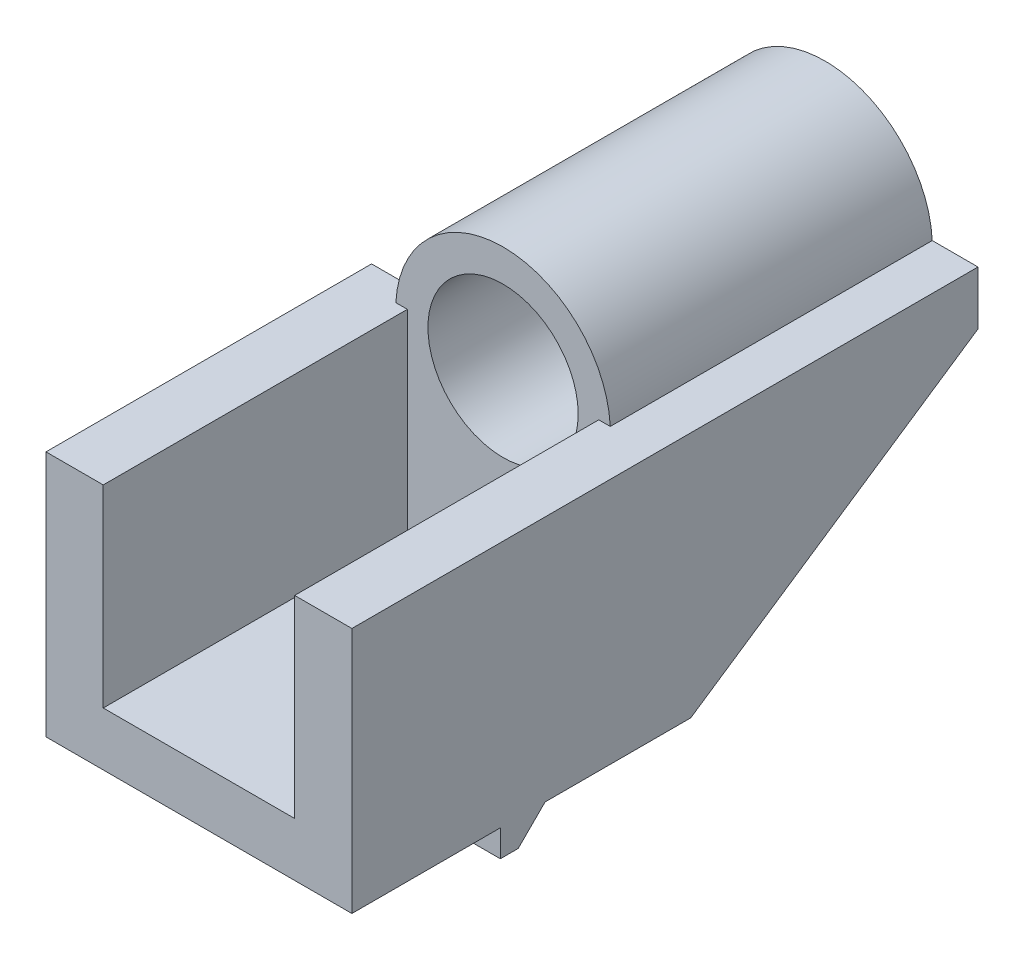
SolidWorks part; units mm, degrees
material "ABS"
ref_plane "Front Plane" through (0, 0, 0) normal (0, 0, 1) x (1, 0, 0)
ref_plane "Top Plane" through (0, 0, 0) normal (0, 1, 0) x (1, 0, 0)
ref_plane "Right Plane" through (0, 0, 0) normal (1, 0, 0) x (0, 0, -1)
sketch "Sketch1" plane through (0, 0, 0) normal (1, 0, 0) x (0, 0, -1)
  line L0 (0, 0) -> (0, -3)
  line L1 (0, -3) -> (-16.0587, -13.8)
  line L2 (-16.0587, -13.8) -> (-35, -13.8)
  line L3 (-35, -13.8) -> (-35, 0)
  line L4 (-35, 0) -> (0, 0)
  dimension "D1" = 35
  dimension "D2" = 3
  dimension "D3" = 13.8
  dimension "D4" = 18.9413
extrude "Boss-Extrude1" add sketch "Sketch1" along normal mid plane 17.1
sketch "Sketch2" plane through (0, 0, 35) normal (0, 0, 1) x (1, 0, 0)
  line L0 (8.55, 0) -> (-8.55, 0) construction
  line L1 (-5.35, 0) -> (5.35, 0)
  line L2 (-5.35, 0) -> (-5.35, -10.8)
  line L3 (-5.35, -10.8) -> (5.35, -10.8)
  line L4 (5.35, 0) -> (5.35, -10.8)
  line L5 (0, -10.8) -> (0, -13.8) construction
  line L6 (8.55, -13.8) -> (-8.55, -13.8) construction
  dimension "D1" = 10.7
  dimension "D2" = 10.8
extrude "Cut-Extrude1" cut sketch "Sketch2" against normal blind 17
sketch "Sketch3" plane through (0, 0, 18) normal (0, 0, 1) x (1, 0, 0)
  line L0 (5.35, 0) -> (-5.35, 0) construction
  circle A0 centre (0, -0.3017) radius 6
  dimension "D1" = 12
  dimension "D2" = 0.3018
extrude "Boss-Extrude2" add sketch "Sketch3" against normal through all
sketch "Sketch4" plane through (0, 0, 18) normal (0, 0, 1) x (1, 0, 0)
  circle A0 centre (0, -0.3017) radius 4.2
  dimension "D1" = 8.4
extrude "Cut-Extrude2" cut sketch "Sketch4" against normal through all
sketch "Sketch8" plane through (8.55, 0, 0) normal (1, 0, 0) x (0, 0, -1)
  line L0 (-26.702, -13.8) -> (-26.702, -15.3)
  line L1 (-35, -13.8) -> (-16.0587, -13.8) construction
  line L2 (-26.702, -15.3) -> (-25.702, -15.3)
  line L3 (-25.702, -15.3) -> (-24.202, -13.8)
  line L4 (-24.202, -13.8) -> (-26.702, -13.8)
  line L5 (-16.0587, -13.8) -> (-15.002, -13.8)
  line L6 (-13, -13.8) -> (-11.046, -10.4288)
  line L7 (-16.0587, -13.8) -> (0, -3) construction
  line L8 (-11.046, -10.4288) -> (-16.0587, -13.8)
  line L9 (-13, -13.8) -> (-14.002, -14.8)
  line L10 (-14.002, -14.8) -> (-15.002, -14.8)
  line L11 (-15.002, -14.8) -> (-15.002, -13.8)
  line L12 (-35, 0) -> (-35, -13.8) construction
  dimension "D1" = 1
  dimension "D2" = 1.5
  dimension "D3" = 2.5
  dimension "D4" = 8.298
  dimension "D5" = 3.0587
  dimension "D6" = 1
  dimension "D7" = 1
  dimension "D8" = 11.7
  dimension "D9" = 165.04
extrude "Boss-Extrude5" add sketch "Sketch8" against normal through all
sketch "Sketch7" plane through (0, -10.8, 0) normal (0, 1, 0) x (1, 0, 0)
  line L0 (0, -25) -> (0, -35) construction
  line L1 (-5.35, -35) -> (5.35, -35) construction
  circle A0 centre (0, -25) radius 2.2
  dimension "D1" = 4.4
  dimension "D2" = 10
extrude "Cut-Extrude3" cut sketch "Sketch7" against normal through all
sketch "Sketch10" plane through (0, 0, 26.702) normal (0, 0, 1) x (1, 0, 0)
  line L1 (-4.053, -13.8) -> (4.053, -13.8)
  line L2 (-4.053, -13.8) -> (-4.053, -15.3)
  line L3 (-4.053, -15.3) -> (4.053, -15.3)
  line L4 (4.053, -13.8) -> (4.053, -15.3)
  line L5 (1.394, -15.3) -> (8.55, -15.3) construction
  line L6 (-8.55, -13.8) -> (-1.394, -13.8) construction
  line L7 (0, -13.8) -> (0, -10.8) construction
  line L8 (8.55, -13.8) -> (-8.55, -13.8) construction
  line L9 (-5.35, -10.8) -> (5.35, -10.8) construction
  dimension "D1" = 8.106
extrude "Cut-Extrude4" cut sketch "Sketch10" against normal up to next
sketch "Sketch11" plane through (0, 0, 15.002) normal (0, 0, 1) x (1, 0, 0)
  line L0 (-8.55, -13.8) -> (8.55, -13.8) construction
  line L1 (-8.55, -14.8) -> (-1.553, -14.8)
  line L2 (-8.55, -14.8) -> (-8.55, -13.8)
  line L3 (-8.55, -13.8) -> (-1.553, -13.8)
  line L4 (-1.553, -14.8) -> (-1.553, -13.8)
  line L6 (8.55, -14.8) -> (1.553, -14.8)
  line L7 (8.55, -14.8) -> (8.55, -13.8)
  line L8 (8.55, -13.8) -> (1.553, -13.8)
  line L9 (1.553, -14.8) -> (1.553, -13.8)
  dimension "D1" = 3.106
extrude "Cut-Extrude5" cut sketch "Sketch11" against normal through all
sketch "Sketch12" plane through (0, -13.8, 0) normal (0, -1, 0) x (1, 0, 0)
  line L0 (-1.553, 13) -> (-5.353, 16.8)
  line L1 (-5.353, 16.8) -> (-5.353, 0)
  line L2 (-5.353, 0) -> (5.353, 0)
  line L3 (5.353, 0) -> (5.353, 16.8)
  line L4 (5.353, 16.8) -> (1.553, 13)
  line L5 (1.553, 13) -> (-1.553, 13)
  line L7 (8.55, 0) -> (5.3591, 0) construction
  dimension "D1" = 3.8
  dimension "D2" = 3.8
  dimension "D3" = 3.8
extrude "Cut-Extrude6" cut sketch "Sketch12" against normal up to surface (10.788 mm away)
sketch "Sketch13" plane through (0, 0, 0) normal (0, 0, -1) x (-1, 0, 0)
  line L0 (-5.3591, -3) -> (-5.353, -10.4288)
  line L1 (-5.353, -10.4288) -> (5.353, -10.4288)
  line L2 (5.353, -10.4288) -> (5.3591, -3)
  arc A0 (-5.3591, -3) -> (5.3591, -3) centre (0, -0.3017) ccw construction
  arc A1 (-5.3591, -3) -> (5.3591, -3) centre (0, -0.3017) ccw
extrude "Cut-Extrude7" cut sketch "Sketch13" against normal up to vertex
sketch "Sketch14" plane through (0, 0, 0) normal (1, 0, 0) x (0, 0, -1)
  line L0 (-13, -13.8) -> (-8.0733, -5.3)
  line L1 (-8.0733, -5.3) -> (-16.8, -5.3)
  line L2 (-13, -13.8) -> (-11.046, -10.4288) construction
  line L3 (-13, -13.8) -> (-16.8, -13.8)
  line L4 (-16.8, -13.8) -> (-16.8, -5.3)
  line L5 (-16.8, -3) -> (-16.8, -10.4288) construction
  dimension "D1" = 8.5
extrude "Boss-Extrude6" add sketch "Sketch14" along normal mid plane 3.106
ref_plane "Plane1" through (-7.4364, -6.5239, 7.4364) normal (0.6009, 0.5271, -0.6009) x (-0.7993, 0.3963, -0.4517)
sketch "Sketch15" plane through (-7.4364, -6.5239, 7.4364) normal (0.6009, 0.5271, -0.6009) x (-0.7993, 0.3963, -0.4517)
  line L0 (-11.246, 0.7337) -> (-11.246, 6.4958)
  line L1 (-11.246, 6.4958) -> (-15.9999, 3.2397)
  line L2 (-15.9999, 3.2397) -> (-11.246, 0.7337)
extrude "Boss-Extrude7" add sketch "Sketch15" against normal up to next
mirror "Mirror1" about plane through (0, 0, 0) normal (1, 0, 0) of "Boss-Extrude7"
sketch "Sketch16" plane through (0, 0, 0) normal (0, 0, -1) x (-1, 0, 0)
  line L0 (5.9924, 0) -> (8.55, 0)
  line L1 (8.55, 0) -> (8.55, -13.8)
  line L2 (8.55, -13.8) -> (5.353, -13.8)
  line L3 (5.353, -13.8) -> (5.353, -3.012)
  arc A0 (5.353, -3.012) -> (5.9924, 0) centre (0, -0.3017) ccw
extrude "Cut-Extrude8" cut sketch "Sketch16" against normal up to vertex
sketch "Sketch17" plane through (8.55, 0, 0) normal (1, 0, 0) x (0, 0, -1)
  line L0 (-11.046, -10.4288) -> (-13, -13.8)
  line L1 (-13, -13.8) -> (-16.0587, -13.8)
  line L2 (-24.202, -13.8) -> (-13, -13.8) construction
  line L3 (-16.0587, -13.8) -> (-11.046, -10.4288)
  line L5 (-11.046, -10.4288) -> (0, -3) construction
extrude "Cut-Extrude9" cut sketch "Sketch17" against normal up to next
